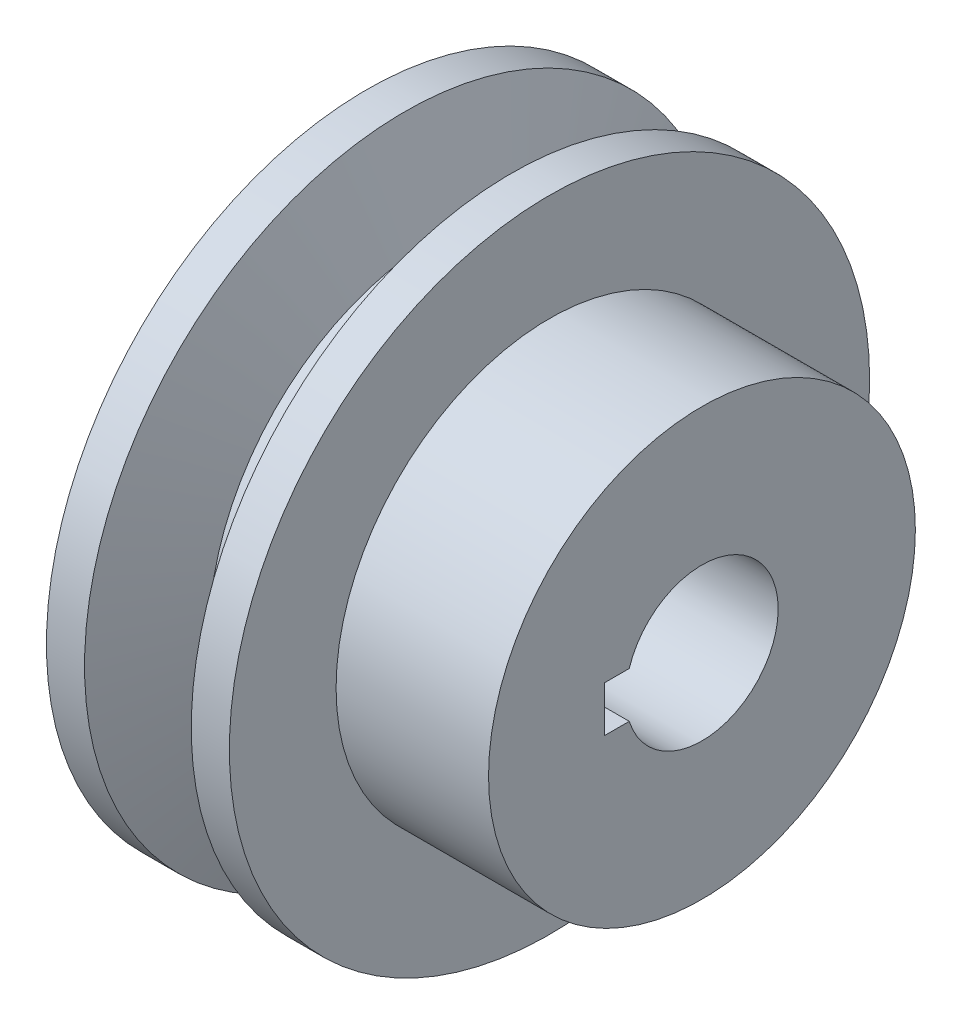
SolidWorks part; units mm, degrees
ref_plane "Front Plane" through (0, 0, 0) normal (0, 0, 1) x (1, 0, 0)
ref_plane "Top Plane" through (0, 0, 0) normal (0, 1, 0) x (1, 0, 0)
ref_plane "Right Plane" through (0, 0, 0) normal (1, 0, 0) x (0, 0, -1)
sketch "Sketch1" plane through (0, 0, 0) normal (0, 0, 1) x (1, 0, 0)
  line L0 (22, 0) -> (0, 0)
  line L1 (0, 0) -> (0, 21)
  line L2 (0, 21) -> (2.5, 21)
  line L3 (2.5, 21) -> (4.6838, 15)
  line L4 (4.6838, 15) -> (7.3162, 15)
  line L5 (7.3162, 15) -> (9.5, 21)
  line L6 (9.5, 21) -> (12, 21)
  line L7 (12, 21) -> (12, 14)
  line L8 (12, 14) -> (22, 14)
  line L9 (22, 14) -> (22, 0)
  line L10 (6, 15) -> (6, 27.658) construction
  dimension "D1" = 22
  dimension "D2" = 12
  dimension "D3" = 40
  dimension "D4" = 7
  dimension "D5" = 21
  dimension "D6" = 14
  dimension "D7" = 15
revolve "Revolve1" add sketch "Sketch1" angle 360 about L0
sketch "Sketch2" plane through (0, 0, 0) normal (-1, 0, 0) x (0, 0, 1)
  line L0 (5, 0) -> (14.5225, 0) construction
  line L1 (6.4, 1.5) -> (6.4, -1.5)
  line L2 (6.4, -1.5) -> (4.7697, -1.5)
  line L3 (6.4, 1.5) -> (4.7697, 1.5)
  arc A0 (4.7697, 1.5) -> (4.7697, -1.5) centre (0, 0) ccw
  dimension "D1" = 10
  dimension "D2" = 6.4
  dimension "D3" = 3
extrude "Cut-Extrude1" cut sketch "Sketch2" against normal through all
